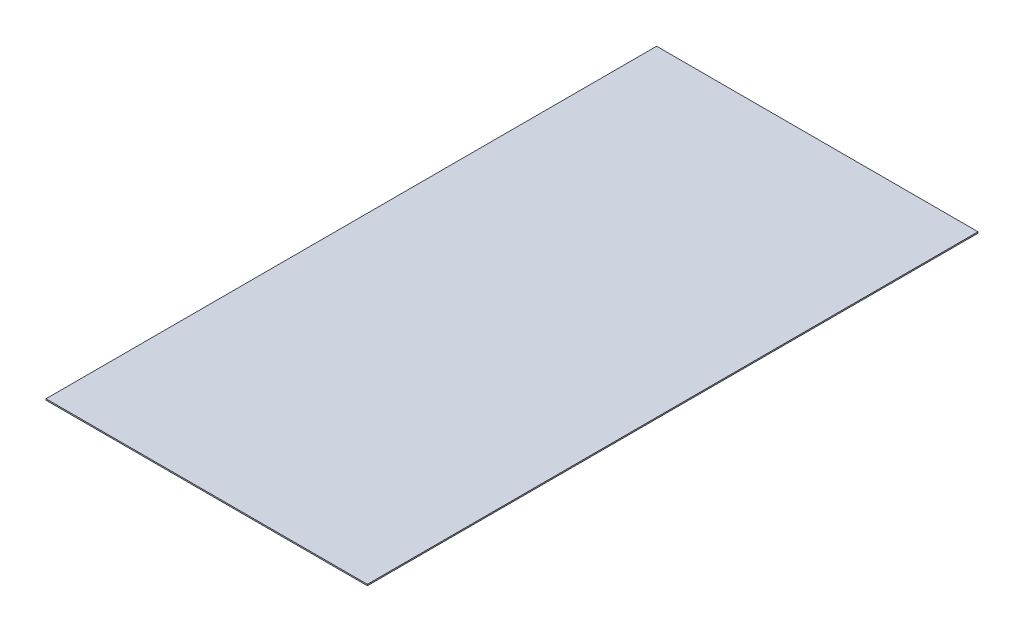
SolidWorks part; units mm, degrees
ref_plane "Front Plane" through (0, 0, 0) normal (0, 0, 1) x (1, 0, 0)
ref_plane "Top Plane" through (0, 0, 0) normal (0, 1, 0) x (1, 0, 0)
ref_plane "Right Plane" through (0, 0, 0) normal (1, 0, 0) x (0, 0, -1)
other "Configuration Table"
sketch "Sketch1" plane through (0, 0, 0) normal (0, 1, 0) x (1, 0, 0)
  line L0 (0, 0) -> (400, 0)
  line L1 (400, 0) -> (400, 760)
  line L2 (400, 760) -> (0, 760)
  line L3 (0, 760) -> (0, 0)
extrude "BLANK_karton_E_dalga_1.6_1" add sketch "Sketch1" along normal blind 1.6 separate body
